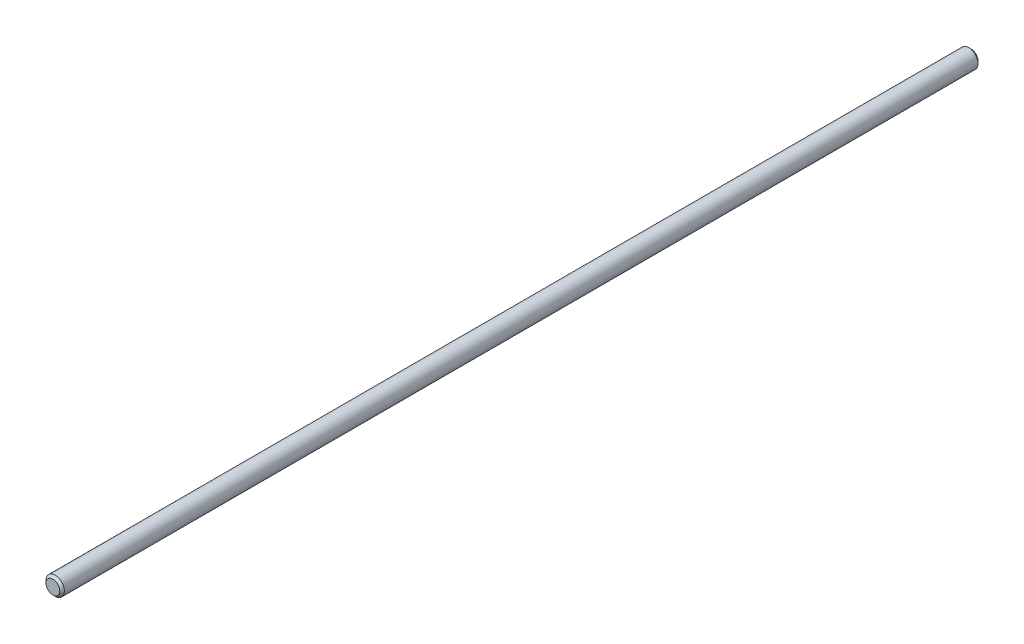
SolidWorks part; units mm, degrees
ref_plane "前视基准面" through (0, 0, 0) normal (0, 0, 1) x (1, 0, 0)
ref_plane "上视基准面" through (0, 0, 0) normal (0, 1, 0) x (1, 0, 0)
ref_plane "右视基准面" through (0, 0, 0) normal (1, 0, 0) x (0, 0, -1)
sketch "草图1" plane through (0, 0, 0) normal (0, 0, 1) x (1, 0, 0)
  circle A0 centre (0, 0) radius 2
extrude "凸台-拉伸1" add sketch "草图1" against normal blind 200
chamfer "倒角1" distance 0.5 angle 45 2 edges at (2, 0, -200) (2, 0, 0)
